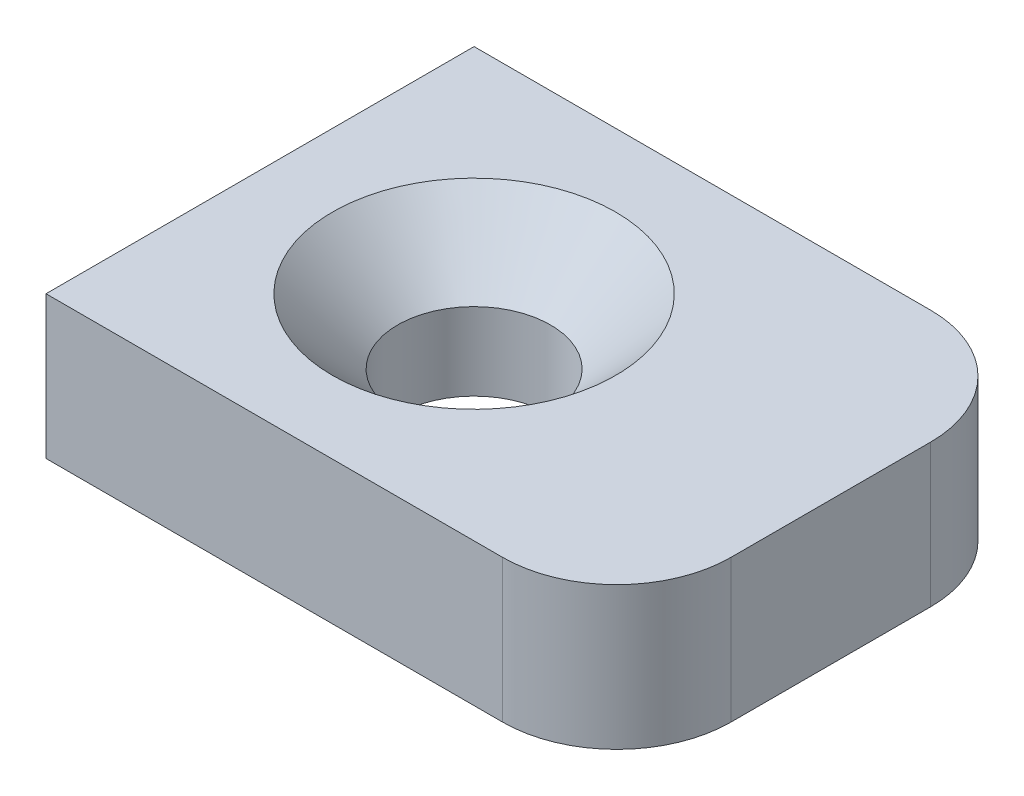
SolidWorks part; units mm, degrees
material "O-1 GS"
ref_plane "Z" through (0, 0, 0) normal (0, 0, 1) x (1, 0, 0)
ref_plane "Y" through (0, 0, 0) normal (0, 1, 0) x (1, 0, 0)
ref_plane "X" through (0, 0, 0) normal (1, 0, 0) x (0, 0, -1)
sketch "Sketch1" plane through (0, 0, 0) normal (0, 1, 0) x (1, 0, 0)
  line L1 (-6.35, 4.7625) -> (6.35, 4.7625)
  line L2 (-6.35, 4.7625) -> (-6.35, -4.7625)
  line L3 (-6.35, -4.7625) -> (6.35, -4.7625)
  line L4 (6.35, 4.7625) -> (6.35, -4.7625)
  point P4 (0, 4.7625)
  point P5 (-6.35, 0)
  point P6 (0, 0)
  dimension "D1" = 9.525
  dimension "D2" = 12.7
extrude "Boss-Extrude1" add sketch "Sketch1" along normal blind 3.175
sketch "Sketch2" plane through (0, 0, 0) normal (0, 1, 0) x (1, 0, 0)
  line L0 (-6.35, 2.286) -> (6.35, 2.286) construction
  line L1 (-6.35, 4.7625) -> (-6.35, -4.7625) construction
  line L2 (6.35, 4.7625) -> (6.35, -4.7625) construction
  line L3 (-1.7463, 0) -> (1.7463, 0) construction
  text T0 "2130-122"
  dimension "D1" = 2.286
extrude "Job+Det#" [suppressed] cut sketch "Sketch2" along normal blind 0.0508
hole_wizard "CSK for M3 Flat Head Machine Screw1" positions "Sketch5" profile "Sketch4" countersink size "M3" standard "ANSI Metric" end condition through all
sketch "Sketch5" plane through (0, 3.175, 0) normal (0, 1, 0) x (1, 0, 0)
  line L0 (-6.35, 4.7625) -> (-6.35, -4.7625) construction
  point P0 (-1.5875, 0)
  dimension "D1" = 4.7625
sketch "Sketch4" plane through (-1.5875, 3.175, 0) normal (1, 0, 0) x (0, 0, 1)
  line L0 (0, 0) -> (0, 3.175)
  line L1 (0, 3.175) -> (1.7, 3.175)
  line L2 (1.7, 3.175) -> (1.7, 1.45)
  line L3 (1.7, 1.45) -> (3.15, 0)
  line L5 (3.15, 0) -> (0, 0)
  line L6 (-1.7, 1.45) -> (-3.15, 0) construction
  line L11 (0, -6.35) -> (0, 107.95) construction
  dimension "Thru Hole Dia." = 3.4
  dimension "Thru Hole Depth" = 3.175
  dimension "Near C'Sink Dia." = 6.3
  dimension "Near C'Sink Angle" = 90
fillet "Fillet1" radius 2.54 2 edges at (6.35, 1.5875, -4.7625) (6.35, 1.5875, 4.7625)
sketch "Sketch6" plane through (0, 3.175, 0) normal (0, 1, 0) x (1, 0, 0)
  line L0 (-9.2056, 11.7905) -> (-9.2056, 4.7879) construction
  line L1 (-9.2056, 11.7905) -> (-9.2056, 4.7879)
  line L2 (-9.2056, 11.7905) -> (-10.6561, 11.7905)
  line L3 (-10.6561, 11.7905) -> (-10.6561, 4.7879)
  line L4 (-10.6561, 4.7879) -> (-9.2056, 4.7879)
